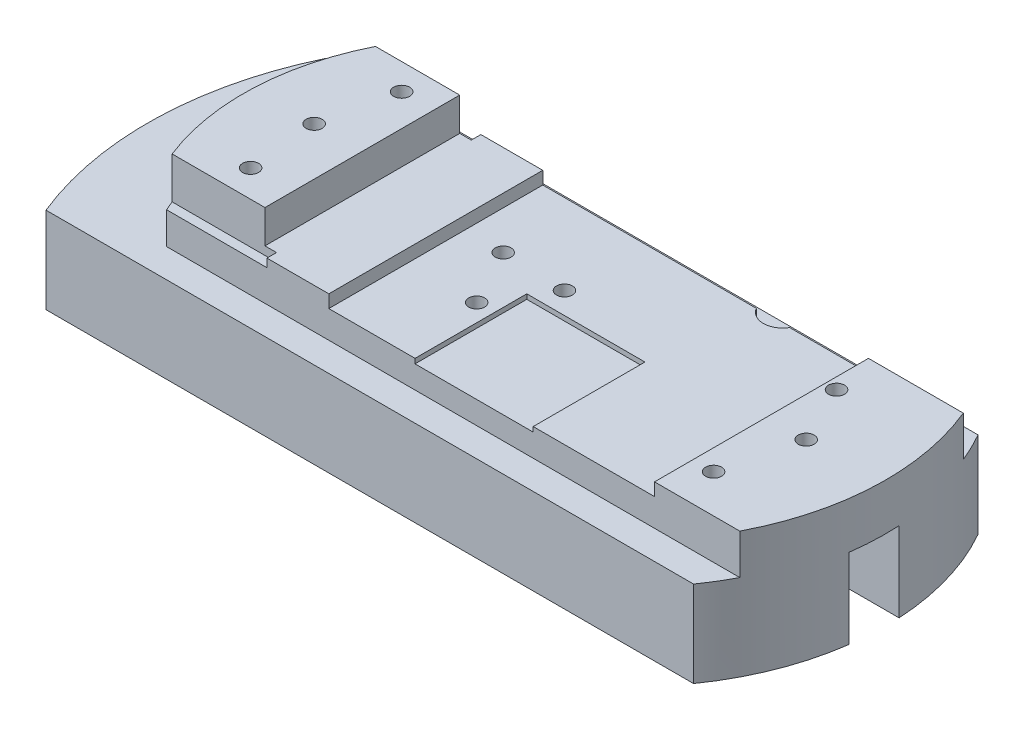
SolidWorks part; units mm, degrees
ref_plane "Front Plane" through (0, 0, 0) normal (0, 0, 1) x (1, 0, 0)
ref_plane "Top Plane" through (0, 0, 0) normal (0, 1, 0) x (1, 0, 0)
ref_plane "Right Plane" through (0, 0, 0) normal (1, 0, 0) x (0, 0, -1)
sketch "Sketch1" plane through (0, 0, 0) normal (0, 1, 0) x (1, 0, 0)
  line L1 (-97.5, -33.5) -> (97.5, -33.5)
  line L2 (-97.5, -33.5) -> (-97.5, 33.5)
  line L3 (-97.5, 33.5) -> (97.5, 33.5)
  line L4 (97.5, -33.5) -> (97.5, 33.5)
  line L5 (-97.5, -33.5) -> (97.5, 33.5) construction
  line L6 (-97.5, 33.5) -> (97.5, -33.5) construction
  point P0 (0, 0)
  dimension "D1" = 67
  dimension "D2" = 195
extrude "Boss-Extrude1" add sketch "Sketch1" along normal blind 50
sketch "Sketch2" plane through (0, 0, 0) normal (0, -1, 0) x (1, 0, 0)
  line L0 (-97.5, -33.5) -> (-97.5, 33.5) construction
  line L1 (97.5, 33.5) -> (97.5, -33.5) construction
  line L2 (97.5, 33.5) -> (88.5, 33.5)
  line L3 (-97.5, 33.5) -> (97.5, 33.5) construction
  line L4 (97.5, -33.5) -> (91.5, -33.5)
  line L5 (97.5, -33.5) -> (-97.5, -33.5) construction
  line L6 (-97.5, 33.5) -> (-91, 33.5)
  line L7 (-97.5, -33.5) -> (-88, -33.5)
  circle A0 centre (18.0922, -3.2198) radius 79.4078
  circle A1 centre (-22.6589, 2.9929) radius 74.8411
  line M7 (97.5, -33.5) -> (97.5, 33.5)
  line M8 (97.5, 33.5) -> (-97.5, 33.5)
  line M9 (-97.5, 33.5) -> (-97.5, -33.5)
  line M10 (-97.5, -33.5) -> (97.5, -33.5)
  dimension "D1" = 9
  dimension "D2" = 6
  dimension "D3" = 6.5
  dimension "D4" = 9.5
extrude "Cut-Extrude1" cut sketch "Sketch2" against normal through all contours A0 M7 M8 | A0 M10 M7 | A1 M9 M10 | A1 M8 M9
sketch "Sketch3" plane through (0, 0, 33.5) normal (0, 0, -1) x (-1, 0, 0)
  line L0 (97.5, 50) -> (63.2, 50)
  line L2 (63.2, 50) -> (63.2, 39.6)
  line L3 (63.2, 39.6) -> (40.2, 39.6)
  line L4 (40.2, 39.6) -> (40.2, 35.6)
  line L5 (40.2, 35.6) -> (-61.8, 35.6)
  line L6 (-91.5, 50) -> (88, 50) construction
  line L10 (97.5, 0) -> (97.5, 50) construction
  line L11 (-61.8, 35.6) -> (-61.8, 39.6)
  line L12 (-61.8, 39.6) -> (-97.5, 39.6)
  line L13 (-97.5, 50) -> (-97.5, 0) construction
  line L14 (-97.5, 39.6) -> (-97.5, 50)
  line L15 (-97.5, 50) -> (63.2, 50)
  line M13 (-88.5, 0) -> (-88.5, 50)
  line M14 (-88.5, 50) -> (91, 50)
  dimension "D1" = 10.4
  dimension "D2" = 34.3
  dimension "D3" = 23
  dimension "D4" = 4
  dimension "D5" = 102
extrude "Cut-Extrude2" cut sketch "Sketch3" along normal through all contours L11 L12 L2 L3 L4 L5 M13 M14
sketch "Sketch4" plane through (0, 50, 0) normal (0, 1, 0) x (1, 0, 0)
  line L0 (-59.5873, 33.5) -> (-59.5873, 30.5)
  line L1 (-63.2, 33.5) -> (-88, 33.5) construction
  line L2 (-59.5873, 30.5) -> (-89.5873, 30.5)
  line L3 (-59.5873, -33.5) -> (-59.5873, -30.5)
  line L4 (-91, -33.5) -> (-63.2, -33.5) construction
  line L5 (-59.5873, -30.5) -> (-92.2617, -30.5)
  line L6 (-59.5873, 33.5) -> (-63.2, 33.5)
  line L7 (-59.5873, -33.5) -> (-63.2, -33.5)
  arc A0 (-88, 33.5) -> (-91, -33.5) centre (-22.6589, -2.9929) ccw construction
  line M5 (-91, -33.5) -> (-63.2, -33.5)
  line M6 (-63.2, -33.5) -> (-63.2, 33.5)
  line M7 (-63.2, 33.5) -> (-88, 33.5)
  arc M8 (-88, 33.5) -> (-91, -33.5) centre (-22.6589, -2.9929) ccw
  dimension "D1" = 3
  dimension "D2" = 3
  dimension "D3" = 30
extrude "Cut-Extrude3" cut sketch "Sketch4" against normal blind 13 contours L2 M6 M7 M8 | L0 L6 L2 M6 | L5 M6 M8 M5 | L7 L3 L5 M6
sketch "Sketch6" plane through (0, 0, 0) normal (0, -1, 0) x (1, 0, 0)
  line L0 (-63.2, -33.5) -> (-97.5, -33.5)
  line L1 (91.5, -33.5) -> (-88, -33.5) construction
  line L2 (-63.2, -33.5) -> (-63.2, 33.5)
  line L3 (-91, 33.5) -> (88.5, 33.5) construction
  line L4 (-63.2, -9) -> (-28.1, -9) construction
  line L5 (-63.2, 8.7) -> (-18.7, 8.7) construction
  line L6 (-63.2, -8.3) -> (-8.2, -8.3) construction
  line L8 (91.5, -33.5) -> (-88, -33.5) construction
  line L9 (-97.5, -33.5) -> (-97.5, 33.5)
  line L10 (-97.5, 33.5) -> (-63.2, 33.5)
  circle A0 centre (-28.1, -9) radius 2.5
  circle A1 centre (-18.7, 8.7) radius 2.5
  circle A2 centre (74.1, -1.7) radius 2.5
  circle A3 centre (68.3, 21.5) radius 2.5
  circle A4 centre (65.3, -20) radius 2.5
  circle A5 centre (-8.2, -8.3) radius 2.5
  circle A6 centre (-76.2, 22) radius 2.5
  circle A7 centre (-78.2, 0.1) radius 2.5
  circle A8 centre (-73.2, -22.3) radius 2.5
  arc A10 (-91, 33.5) -> (-88, -33.5) centre (-22.6589, 2.9929) ccw construction
  dimension "D2" = 5
  dimension "D3" = 35.1
  dimension "D4" = 34.3
  dimension "D5" = 44.5
  dimension "D6" = 24.5
  dimension "D7" = 55
  dimension "D8" = 42.2
  dimension "D9" = 137.3
  dimension "D10" = 128.5
  dimension "D11" = 131.5
  dimension "D12" = 10
  dimension "D13" = 15
  dimension "D14" = 13
  dimension "D15" = 11.2
  dimension "D16" = 33.6
  dimension "D17" = 55.5
  dimension "D18" = 31.8
  dimension "D19" = 55
  dimension "D20" = 13.5
  dimension "D21" = 25.2
extrude "Cut-Extrude4" cut sketch "Sketch6" against normal through all contours A0 | A5 | A1 | A6 | A7 | A8 | A4 | A2 | A3
sketch "Sketch7" plane through (0, 35.6, 0) normal (0, 1, 0) x (1, 0, 0)
  line L1 (-13.2, 1.5) -> (23.8, 1.5)
  line L2 (-13.2, 1.5) -> (-13.2, -33.5)
  line L3 (-13.2, -33.5) -> (23.8, -33.5)
  line L4 (23.8, 1.5) -> (23.8, -33.5)
  line L8 (-63.2, 30.5) -> (-63.2, -30.5) construction
  line L9 (-63.2, 30.5) -> (-63.2, -30.5) construction
  line L10 (-40.2, -33.5) -> (61.8, -33.5) construction
  dimension "D1" = 50
  dimension "D2" = 87
  dimension "D3" = 35
extrude "Cut-Extrude5" cut sketch "Sketch7" against normal blind 1.5
sketch "Sketch8" plane through (0, 50, 0) normal (0, 1, 0) x (1, 0, 0)
  line L0 (-59.5873, -33.5) -> (-97.5, -33.5)
  line L1 (-97.5, -33.5) -> (-97.5, 33.5)
  line L3 (-97.5, 33.5) -> (31.9, 33.5)
  line L6 (31.9, 36.5) -> (31.9, 30.5)
  line L7 (31.9, 33.5) -> (37.0962, 33.5)
  line L10 (-59.5873, 33.5) -> (-88, 33.5) construction
  line L11 (-40.2, 33.5) -> (61.8, 33.5) construction
  circle A1 centre (31.9, 36.5) radius 6
  arc A2 (-89.5873, 30.5) -> (-92.2617, -30.5) centre (-22.6589, -2.9929) ccw construction
  dimension "D1" = 12
  dimension "D2" = 129.4
extrude "Cut-Extrude6" cut sketch "Sketch8" against normal blind 18.5 contours L6 A1 L7 | L3 A1 L6
sketch "Sketch9" plane through (0, 0, 0) normal (0, -1, 0) x (1, 0, 0)
  line L0 (-100, 1) -> (-100, -1) construction
  line L1 (-91, 33.5) -> (88.5, 33.5) construction
  line L2 (-90, -28.5) -> (0, -28.5)
  line L3 (-90, -28.5) -> (-90, 28.5)
  line L4 (-90, 28.5) -> (0, 28.5)
  line L5 (0, -28.5) -> (0, 28.5)
  line L6 (-90, -28.5) -> (0, 28.5) construction
  line L7 (-90, 28.5) -> (0, -28.5) construction
  line L8 (0, 28.5) -> (0, 7.5)
  line L9 (0, -7.5) -> (97.5, -7.5)
  line L10 (0, -7.5) -> (0, 7.5)
  line L11 (0, 7.5) -> (97.5, 7.5)
  line L12 (97.5, -7.5) -> (97.5, 7.5)
  line L13 (0, -7.5) -> (97.5, 7.5) construction
  line L14 (0, 7.5) -> (97.5, -7.5) construction
  line L15 (0, -7.5) -> (0, -28.5)
  circle A1 centre (-100, 20) radius 19
  circle A2 centre (-100, -20) radius 19
  arc A3 (91.5, -33.5) -> (88.5, 33.5) centre (18.0922, -3.2198) ccw construction
  circle A4 centre (2.3966, -9.8966) radius 2.3966
  circle A5 centre (2.3966, 9.8966) radius 2.3966
  circle A6 centre (-81.5859, 30.8966) radius 2.3966
  circle A7 centre (-81.5859, -30.8966) radius 2.3966
  circle A8 centre (-92.3966, 0) radius 2.3966
  circle A9 centre (-2.3966, 26.1034) radius 2.3966
  circle A10 centre (-2.3966, -26.1034) radius 2.3966
  point P0 (-45, 0)
  point P4 (-100, -1)
  point P5 (-100, 1)
  point P10 (-100, 0)
  point P20 (48.75, 0)
  circle M1 centre (-8.2, -8.3) radius 2.5
  circle M2 centre (-18.7, 8.7) radius 2.5
  circle M3 centre (-76.2, 22) radius 2.5
  circle M5 centre (-73.2, -22.3) radius 2.5
  circle M6 centre (65.3, -20) radius 2.5
  circle M7 centre (74.1, -1.7) radius 2.5
  circle M8 centre (68.3, 21.5) radius 2.5
  circle M9 centre (-28.1, -9) radius 2.5
  line M10 (-88, -33.5) -> (91.5, -33.5)
  arc M11 (91.5, -33.5) -> (88.5, 33.5) centre (18.0922, -3.2198) ccw
  line M12 (88.5, 33.5) -> (-91, 33.5)
  arc M13 (-91, 33.5) -> (-88, -33.5) centre (-22.6589, 2.9929) ccw
  dimension "D2" = 38
  dimension "D4" = 2
  dimension "D5" = 100
  dimension "D6" = 5
  dimension "D7" = 10
  dimension "D8" = 15
extrude "Cut-Extrude7" cut sketch "Sketch9" against normal offset from surface (25 mm away) 25 contours L4 A1 L3 M12 M3 | L3 A1 L4 | L2 A2 L3 | A2 L2 L3 M10 M5 | A2 L2 L4 A1 L3 M6 M11 M8 M2 M9 M7 M1 | L11 L5 L9 M2 M1 M11 M7 | A8 L3 A1 | A8 A2 L3 | A7 L2 A2 | A4 L9 L15 | A5 L5 L11 | A6 A1 L4 | A9 | A10 M13
sketch "Sketch10" plane through (0, 25, 0) normal (0, -1, 0) x (1, 0, 0)
  line L0 (-86.2229, 42.5) -> (83.0176, 42.5)
  line L1 (-1.6027, 42.5) -> (-1.6027, -42.5) construction
  line L2 (87.1042, -42.5) -> (-82.0861, -42.5)
  line L3 (-91, 33.5) -> (88.5, 33.5)
  line L4 (91.5, -33.5) -> (-120.9438, -33.5)
  line L5 (-91, 33.5) -> (-86.6303, 33.5) construction
  line L6 (-86.2229, 42.5) -> (-119.7714, 42.5)
  line L7 (-82.0861, -42.5) -> (-117.1155, -42.5)
  circle A0 centre (-22.6589, 2.9929) radius 74.8411
  arc A1 (-97.4778, 1.1682) -> (-97.3835, -1.181) centre (-22.6589, 2.9929) ccw construction
  circle A2 centre (18.0922, -3.2198) radius 79.4078
  arc A3 (91.5, -33.5) -> (97.3846, -7.5) centre (18.0922, -3.2198) ccw construction
  circle A4 centre (-100, 20) radius 19
  circle A5 centre (-100, -20) radius 19
  arc A6 (-86.6303, -33.5) -> (-83.6484, -29.6761) centre (-100, -20) ccw construction
  arc A8 (-97.4778, 1.1682) -> (-93.2482, 2.2401) centre (-100, 20) ccw construction
  circle A9 centre (-22.6589, 2.9929) radius 104.8411
  point P14 (-1.6027, 0)
  dimension "D1" = 85
  dimension "D2" = 30
extrude "Boss-Extrude2" add sketch "Sketch10" along normal up to surface (25 mm away) contours A4 L3 A2 L0 A0 | L1 L0 A2 L3 | L0 L1 L3 A0 | L3 A9 L0 A0 | A9 L3 A2 L0 | A9 L2 A2 L4 | L2 A9 L4 A0 | L4 L1 L2 A0 | L1 L4 A2 L2 | A5 A0 L2 A2 L4 | L6 A9 L4 A5 A0 A4 | L4 A9 A2 A0 A5
sketch "Sketch11" plane through (0, 25, 0) normal (0, 1, 0) x (1, 0, 0)
  line L0 (83.0176, -42.5) -> (-86.2229, -42.5)
  line L1 (87.1042, 42.5) -> (-117.1155, 42.5)
  line L2 (-119.7714, -42.5) -> (83.0176, -42.5) construction
  line L3 (87.1042, 42.5) -> (-117.1155, 42.5) construction
  line L4 (88.5, -33.5) -> (-91, -33.5)
  line L5 (-88, 33.5) -> (91.5, 33.5)
  line L6 (-86.2229, -42.5) -> (-119.7714, -42.5)
  circle A0 centre (-22.6589, -2.9929) radius 74.8411
  circle A1 centre (18.0922, 3.2198) radius 79.4078
  arc A2 (88.5, -33.5) -> (91.5, 33.5) centre (18.0922, 3.2198) ccw construction
  arc A3 (-89.5873, 30.5) -> (-92.2617, -30.5) centre (-22.6589, -2.9929) ccw construction
  circle A5 centre (-22.6589, -2.9929) radius 104.8411
  arc A6 (-117.1155, 42.5) -> (-119.7714, -42.5) centre (-22.6589, -2.9929) ccw construction
extrude "Boss-Extrude3" add sketch "Sketch11" along normal blind 2
